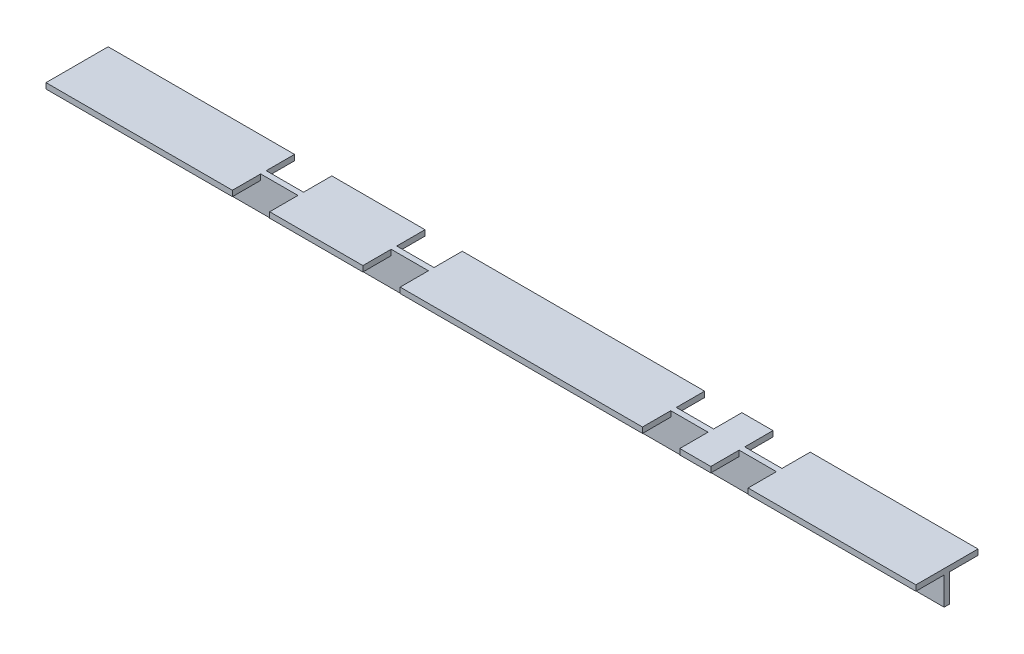
SolidWorks part; units mm, degrees
ref_plane "Front Plane" through (0, 0, 0) normal (0, 0, 1) x (1, 0, 0)
ref_plane "Top Plane" through (0, 0, 0) normal (0, 1, 0) x (1, 0, 0)
ref_plane "Right Plane" through (0, 0, 0) normal (1, 0, 0) x (0, 0, -1)
sketch "T" plane through (0, 0, 0) normal (1, 0, 0) x (0, 0, -1)
  line L0 (50, 0) -> (50, -54) construction
  line L1 (0, 0) -> (100, 0)
  line L2 (0, 0) -> (0, -9)
  line L3 (0, -9) -> (45.5, -9)
  line L4 (100, 0) -> (100, -9)
  line L6 (45.5, -9) -> (45.5, -54)
  line L7 (45.5, -54) -> (54.5, -54)
  line L8 (54.5, -9) -> (54.5, -54)
  line L9 (54.5, -9) -> (100, -9)
  dimension "D1" = 100
  dimension "D2" = 45
  dimension "D3" = 9
  dimension "D4" = 9
extrude "Boss-Extrude1" add sketch "T" along normal blind 1400
sketch "Sketch1" plane through (0, -9, 0) normal (0, -1, 0) x (-1, 0, 0)
  line L0 (-1400, 45.5) -> (0, 45.5) construction
  line L1 (-360, 45.5) -> (-300, 45.5)
  line L2 (-360, 45.5) -> (-360, 0)
  line L3 (-360, 0) -> (-300, 0)
  line L4 (-300, 45.5) -> (-300, 0)
  line L5 (-1400, 0) -> (0, 0) construction
  line L6 (-1400, 45.5) -> (0, 45.5) construction
  line L7 (-570, 45.5) -> (-510, 45.5)
  line L8 (-570, 45.5) -> (-570, 0)
  line L9 (-570, 0) -> (-510, 0)
  line L10 (-510, 45.5) -> (-510, 0)
  line L11 (-1130, 45.5) -> (-1070, 45.5)
  line L12 (-1130, 45.5) -> (-1130, 0)
  line L13 (-1130, 0) -> (-1070, 0)
  line L14 (-1070, 45.5) -> (-1070, 0)
  line L15 (-1400, 100) -> (0, 100) construction
  line L16 (-1130, 100) -> (-1070, 100)
  line L17 (-1130, 100) -> (-1130, 54.5)
  line L18 (-1130, 54.5) -> (-1070, 54.5)
  line L19 (-1070, 100) -> (-1070, 54.5)
  line L20 (-1400, 54.5) -> (0, 54.5) construction
  line L21 (0, 54.5) -> (0, 100) construction
  line L22 (-570, 100) -> (-510, 100)
  line L23 (-570, 100) -> (-570, 54.5)
  line L24 (-570, 54.5) -> (-510, 54.5)
  line L25 (-510, 100) -> (-510, 54.5)
  line L26 (-360, 100) -> (-300, 100)
  line L27 (-360, 100) -> (-360, 54.5)
  line L28 (-360, 54.5) -> (-300, 54.5)
  line L29 (-300, 100) -> (-300, 54.5)
  line L30 (-1400, 0) -> (0, 0) construction
  line L31 (-1020, 0) -> (-960, 0)
  line L32 (-1020, 0) -> (-1020, 45.5)
  line L33 (-1020, 45.5) -> (-960, 45.5)
  line L34 (-960, 0) -> (-960, 45.5)
  line L35 (-1400, 100) -> (0, 100) construction
  line L36 (-1020, 54.5) -> (-960, 54.5)
  line L37 (-1020, 54.5) -> (-1020, 100)
  line L38 (-1020, 100) -> (-960, 100)
  line L39 (-960, 54.5) -> (-960, 100)
  point P36 (-570, 77.25)
  point P37 (-1070, 77.25)
  dimension "D1" = 60
  dimension "D2" = 300
  dimension "D3" = 150
  dimension "D4" = 60
  dimension "D5" = 60
  dimension "D6" = 500
  dimension "D7" = 60
  dimension "D8" = 50
extrude "Cut-Extrude1" cut sketch "Sketch1" against normal through all contours L19 L18 L17 L16
equation "\"D4@Sketch1\"=\"D1@Sketch1\""
equation "\"D5@Sketch1\"=\"D1@Sketch1\""
equation "\"D7@Sketch1\"=\"D1@Sketch1\""
